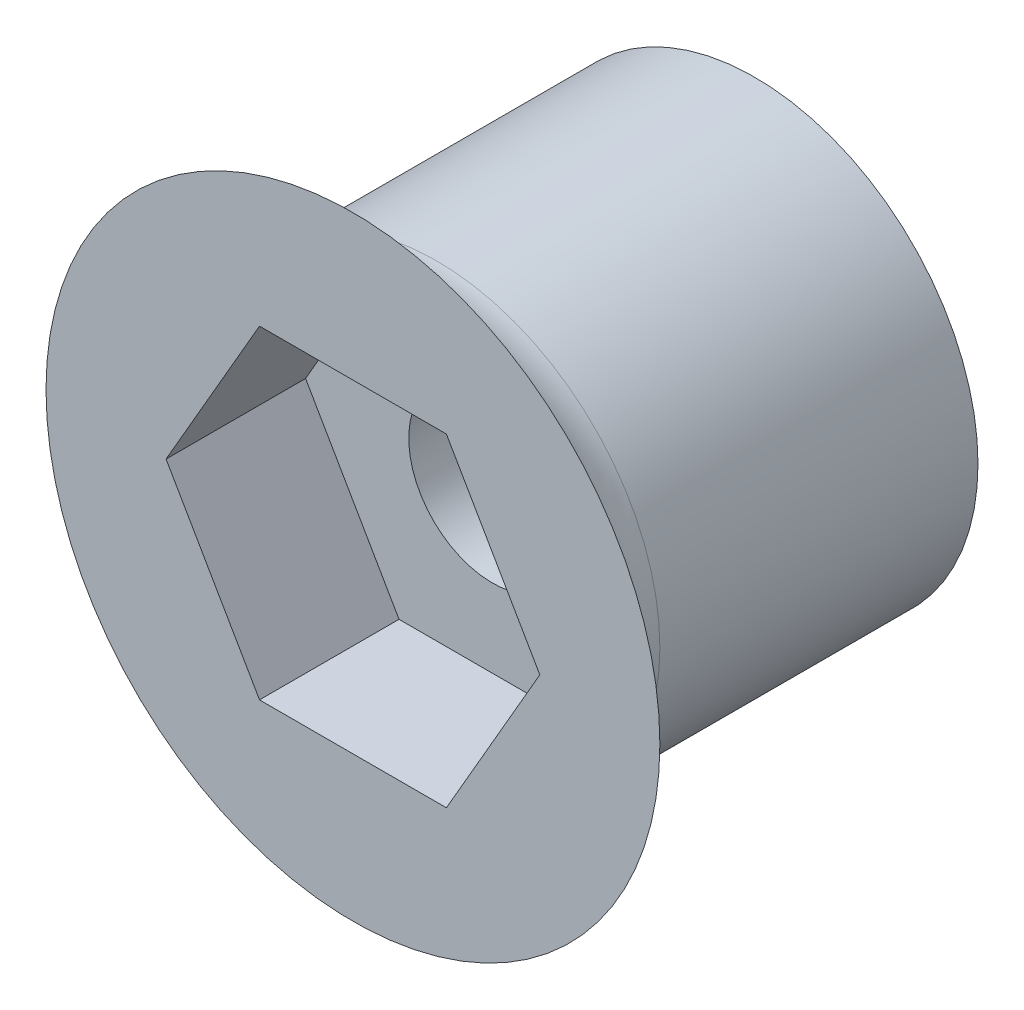
SolidWorks part; units mm, degrees
ref_plane "Front Plane" through (0, 0, 0) normal (0, 0, 1) x (1, 0, 0)
ref_plane "Top Plane" through (0, 0, 0) normal (0, 1, 0) x (1, 0, 0)
ref_plane "Right Plane" through (0, 0, 0) normal (1, 0, 0) x (0, 0, -1)
sketch "Sketch1" plane through (0, 0, 0) normal (0, 1, 0) x (1, 0, 0)
  line L0 (0, 0) -> (0, 7.2) construction
  line L1 (0, 0) -> (-4, 0) construction
  line L2 (-1.5, 0) -> (-4, 0)
  line L3 (-1.5, 0) -> (-1.5, 7.2)
  line L4 (-1.5, 7.2) -> (-4, 7.2)
  line L5 (-4, 1.5) -> (-4, 7.2)
  line L6 (-4, 0) -> (-5.5, 0)
  line L7 (-5.5, 0) -> (-5.5, 1.5) construction
  line L8 (-5.5, 1.5) -> (-4, 1.5) construction
  arc A0 (-5.5, 0) -> (-4, 1.5) centre (-5.5, 1.5) ccw
  point P10 (0, 7.2)
  dimension "D5" = 3
  dimension "D1" = 1.5
  dimension "D2" = 4
  dimension "D3" = 7.2
  dimension "D4" = 1.5
revolve "Revolve1" add sketch "Sketch1" angle 360 about L0
sketch "Sketch2" plane through (0, 0, 0) normal (0, 0, 1) x (1, 0, 0)
  line L1 (1.6743, 2.9) -> (-1.6743, 2.9)
  line L2 (-1.6743, 2.9) -> (-3.3486, 0)
  line L3 (-3.3486, 0) -> (-1.6743, -2.9)
  line L4 (-1.6743, -2.9) -> (1.6743, -2.9)
  line L5 (1.6743, -2.9) -> (3.3486, 0)
  line L6 (3.3486, 0) -> (1.6743, 2.9)
  circle A0 centre (0, 0) radius 2.9 construction
  dimension "D1" = 5.8
extrude "Cut-Extrude1" cut sketch "Sketch2" against normal blind 2.5
